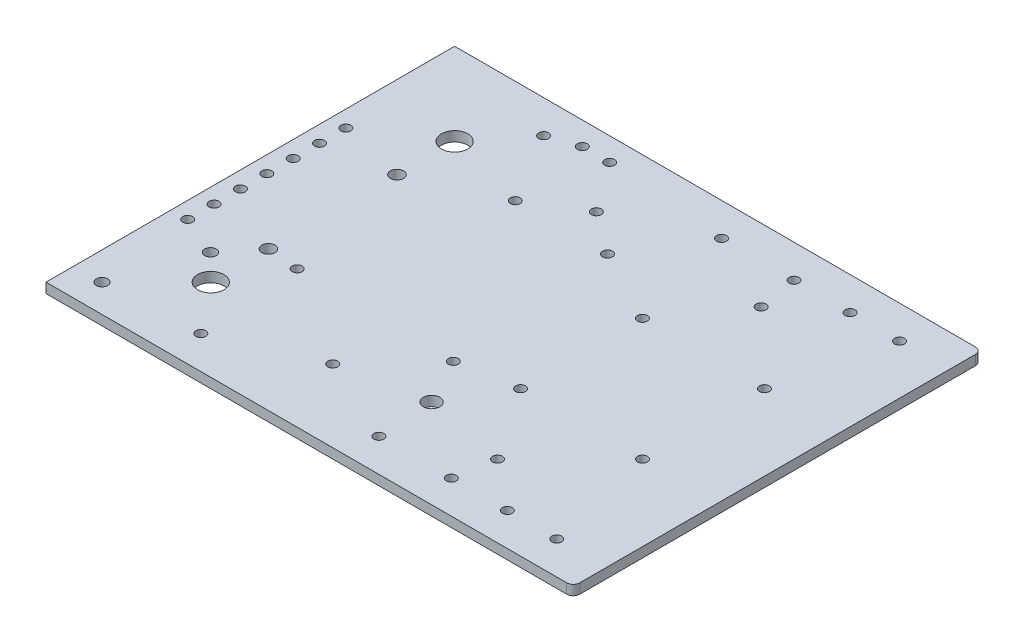
SolidWorks part; units mm, degrees
ref_plane "Front" through (0, 0, 0) normal (0, 0, 1) x (1, 0, 0)
ref_plane "Top" through (0, 0, 0) normal (0, 1, 0) x (1, 0, 0)
ref_plane "Right" through (0, 0, 0) normal (1, 0, 0) x (0, 0, -1)
sketch "草圖1" plane through (0, 0, 0) normal (0, 1, 0) x (1, 0, 0)
  line L1 (0, -62) -> (160, -62)
  line L2 (0, -62) -> (0, 62)
  line L3 (0, 62) -> (160, 62)
  line L4 (160, -62) -> (160, 62)
  dimension "D1" = 124
  dimension "D2" = 160
extrude "填料-伸長1" add sketch "草圖1" along normal blind 3
sketch "草圖2" plane through (0, 3, 0) normal (0, 1, 0) x (1, 0, 0)
  line L0 (160, 62) -> (0, 62) construction
  line L1 (113, 52) -> (130, 52) construction
  line L2 (160, -62) -> (160, 62) construction
  line L3 (0, -62) -> (160, -62) construction
  line L4 (113, 52) -> (130, 52) construction
  line L5 (113, 52) -> (113, -52) construction
  line L6 (113, -52) -> (130, -52) construction
  line L7 (130, 52) -> (130, -52) construction
  circle A0 centre (113, 52) radius 1.5
  circle A1 centre (130, 52) radius 1.5
  circle A2 centre (113, -52) radius 1.5
  circle A3 centre (130, -52) radius 1.5
  dimension "D1" = 10
  dimension "D3" = 3
  dimension "D5" = 30
  dimension "D2" = 17
  dimension "D6" = 10
extrude "除料-伸長1" cut sketch "草圖2" against normal blind 10
sketch "草圖3" plane through (0, 0, 0) normal (0, -1, 0) x (1, 0, 0)
  line L0 (25, 19.5) -> (25, -19.5) construction
  line L1 (0, 0) -> (25, 0) construction
  line L2 (0, -62) -> (0, 62) construction
  circle A0 centre (25, 19.5) radius 2
  circle A1 centre (25, -19.5) radius 2
  dimension "D1" = 4
  dimension "D2" = 4
  dimension "D3" = 39
  dimension "D4" = 25
extrude "除料-伸長2" cut sketch "草圖3" against normal through all
sketch "草圖4" plane through (0, 3, 0) normal (0, 1, 0) x (1, 0, 0)
  line L0 (0, 62) -> (0, -62) construction
  line L1 (160, 62) -> (0, 62) construction
  circle A0 centre (5, 24) radius 1.5
  dimension "D1" = 3
  dimension "D2" = 5
  dimension "D3" = 38
extrude "除料-伸長3" cut sketch "草圖4" against normal blind 10
pattern_linear "直線複製排列1" count 7 spacing 8 along (0, 0, 1) of "除料-伸長3"
sketch "草圖6" plane through (0, 3, 0) normal (0, 1, 0) x (1, 0, 0)
  circle A0 centre (100, 19) radius 1.5
  circle A1 centre (137, 19) radius 1.5
  circle A2 centre (100, -18) radius 1.5
  circle A3 centre (137, -18) radius 1.5
extrude "除料-伸長4" cut sketch "草圖6" against normal blind 10
sketch "草圖7" plane through (0, 3, 0) normal (0, 1, 0) x (1, 0, 0)
  circle A0 centre (49.8, 30.6) radius 1.5
  circle A1 centre (77.8, 30.6) radius 1.5
  circle A2 centre (34.6, -20.4) radius 1.5
  circle A3 centre (82.6, -21) radius 1.5
extrude "除料-伸長5" cut sketch "草圖7" against normal blind 10
sketch "草圖8" plane through (0, 3, 0) normal (0, 1, 0) x (1, 0, 0)
  circle A0 centre (37, 52) radius 1.5
  circle A1 centre (145, 52) radius 1.5
  circle A2 centre (37, -52) radius 1.5
  circle A3 centre (145, -52) radius 1.5
extrude "除料-伸長6" cut sketch "草圖8" against normal blind 10
sketch "草圖9" plane through (0, 3, 0) normal (0, 1, 0) x (1, 0, 0)
  circle A0 centre (91, -52) radius 1.5
  circle A1 centre (91, 52) radius 1.5
extrude "除料-伸長7" cut sketch "草圖9" against normal blind 10 contours A0 | A1
sketch "草圖10" plane through (0, 3, 0) normal (0, 1, 0) x (1, 0, 0)
  line L0 (160, 62) -> (0, 62) construction
  line L1 (0, 62) -> (0, -62) construction
  line L2 (0, -62) -> (160, -62) construction
  circle A0 centre (25, 37) radius 4
  circle A1 centre (25, -37) radius 4
  dimension "D1" = 8
  dimension "D4" = 25
  dimension "D5" = 25
  dimension "D6" = 8
  dimension "D2" = 25
  dimension "D3" = 25
extrude "除料-伸長8" cut sketch "草圖10" against normal blind 10
sketch "草圖11" plane through (0, 3, 0) normal (0, 1, 0) x (1, 0, 0)
  line L0 (107, -39) -> (117, -39) construction
  line L1 (117, -39) -> (126, -39) construction
  line L2 (0, -62) -> (160, -62) construction
  line L3 (160, -62) -> (160, 62) construction
  line L4 (160, 62) -> (0, 62) construction
  line L5 (117, 39) -> (126, 39) construction
  circle A0 centre (117, -39) radius 1.5
  circle A1 centre (126, -39) radius 1.5
  circle A2 centre (107, -39) radius 2.5
  circle A3 centre (117, 39) radius 1.5
  circle A4 centre (126, 39) radius 1.5
  dimension "D1" = 3
  dimension "D2" = 3
  dimension "D3" = 5
  dimension "D5" = 34
  dimension "D8" = 3
  dimension "D9" = 3
  dimension "D10" = 34
  dimension "D11" = 23
  dimension "D4" = 23
  dimension "D6" = 9
  dimension "D7" = 10
  dimension "D12" = 9
extrude "除料-伸長9" [suppressed] cut sketch "草圖11" against normal blind 10
fillet "圓角1" radius 2 2 edges at (160, 1.5, 62) (160, 1.5, -62)
sketch "草圖12" plane through (0, 0, 0) normal (0, -1, 0) x (1, 0, 0)
  line L0 (115, 0) -> (160, 0) construction
  line L1 (65, 40) -> (115, 40) construction
  line L2 (65, 40) -> (65, -40) construction
  line L3 (65, -40) -> (115, -40) construction
  line L4 (115, 40) -> (115, -40) construction
  line L5 (160, 60) -> (160, -60) construction
  circle A0 centre (65, 40) radius 1.5
  circle A1 centre (115, 40) radius 1.5
  circle A2 centre (65, -40) radius 1.5
  circle A3 centre (115, -40) radius 1.5
  dimension "D4" = 3
  dimension "D1" = 50
  dimension "D2" = 80
  dimension "D3" = 45
extrude "除料-伸長10" cut sketch "草圖12" against normal blind 10
sketch "草圖13" plane through (0, 0, 0) normal (0, -1, 0) x (1, 0, 0)
  circle A0 centre (8.5, 53.5) radius 1.75
  circle A1 centre (17.1, 29.2) radius 1.75
  dimension "D1" = 3.5
  dimension "D2" = 3.5
extrude "除料-伸長11" cut sketch "草圖13" against normal blind 70
sketch "草圖14" plane through (0, 0, 0) normal (0, -1, 0) x (1, 0, 0)
  circle A0 centre (54.05, -55) radius 1.5
  circle A1 centre (45.75, -55) radius 1.5
  dimension "D1" = 3
  dimension "D2" = 3
extrude "除料-伸長12" cut sketch "草圖14" against normal blind 4
sketch "草圖15" plane through (0, 0, 0) normal (0, -1, 0) x (1, 0, 0)
  line L1 (160, 60) -> (160, -60) construction
  line L2 (0, 62) -> (158, 62) construction
  circle A0 centre (90, 35) radius 2.5
  dimension "D1" = 27
  dimension "D2" = 70
  dimension "D3" = 5
extrude "除料-伸長13" cut sketch "草圖15" against normal blind 10
